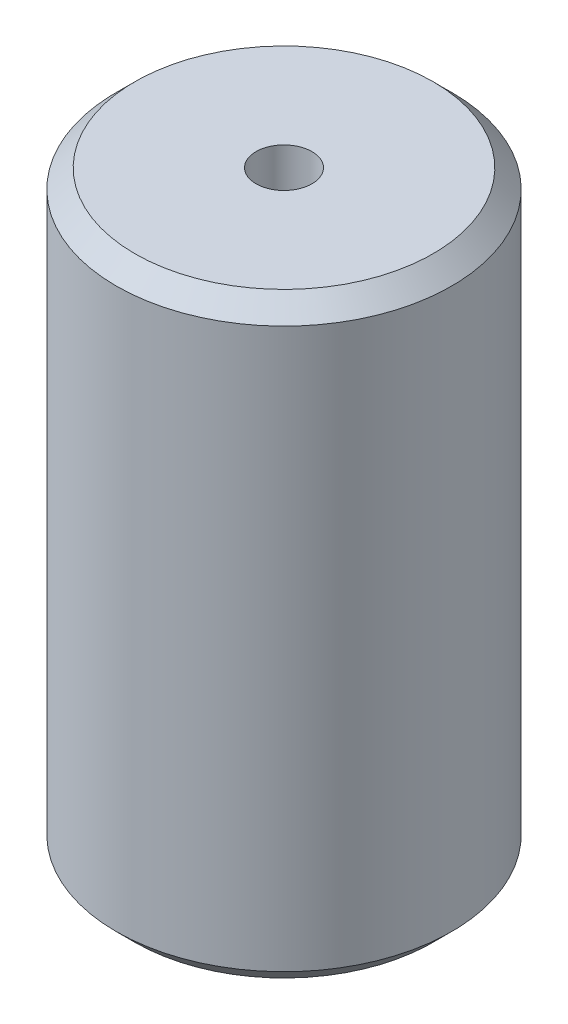
SolidWorks part; units mm, degrees
ref_plane "Front Plane" through (0, 0, 0) normal (0, 0, 1) x (1, 0, 0)
ref_plane "Top Plane" through (0, 0, 0) normal (0, 1, 0) x (1, 0, 0)
ref_plane "Right Plane" through (0, 0, 0) normal (1, 0, 0) x (0, 0, -1)
sketch "Sketch1" plane through (0, 0, 0) normal (0, 1, 0) x (1, 0, 0)
  circle A0 centre (0, 0) radius 9
  circle A1 centre (0, 0) radius 1.5
  dimension "D1" = 18
  dimension "D2" = 3
extrude "Boss-Extrude1" add sketch "Sketch1" along normal blind 32
chamfer "Chamfer1" distance 1 angle 45 2 edges at (0, 0, 9) (0, 32, 9)
